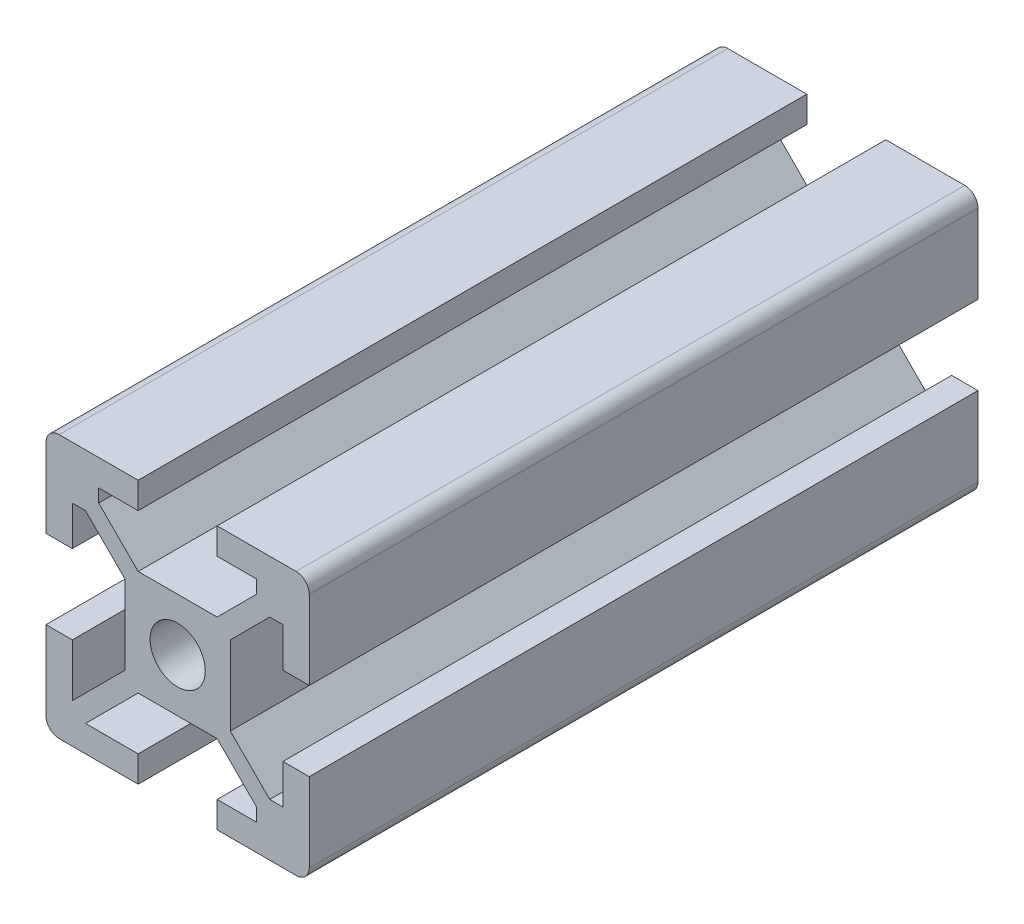
SolidWorks part; units mm, degrees
ref_plane "Front Plane" through (0, 0, 0) normal (0, 0, 1) x (1, 0, 0)
ref_plane "Top Plane" through (0, 0, 0) normal (0, 1, 0) x (1, 0, 0)
ref_plane "Right Plane" through (0, 0, 0) normal (1, 0, 0) x (0, 0, -1)
sketch "Sketch1" plane through (0, 0, 0) normal (0, 0, 1) x (1, 0, 0)
  line L0 (0, 10) -> (0, -10) construction
  line L1 (10, 10) -> (-10, 10)
  line L2 (10, 10) -> (10, -10)
  line L3 (10, -10) -> (-10, -10)
  line L4 (-10, 10) -> (-10, -10)
  line L5 (10, 10) -> (-10, -10) construction
  line L6 (10, -10) -> (-10, 10) construction
  line L7 (-10, 0) -> (10, 0) construction
  line L8 (-4, 3) -> (-8, 7)
  line L9 (6, 6) -> (-6, 6)
  line L10 (6, 6) -> (6, -6)
  line L11 (6, -6) -> (-6, -6)
  line L12 (-6, 6) -> (-6, -6)
  line L13 (6, 6) -> (-6, -6) construction
  line L14 (6, -6) -> (-6, 6) construction
  line L15 (4, 4) -> (-4, 4)
  line L16 (4, 4) -> (4, -4)
  line L17 (4, -4) -> (-4, -4)
  line L18 (-4, 4) -> (-4, -4)
  line L19 (4, 4) -> (-4, -4) construction
  line L20 (4, -4) -> (-4, 4) construction
  line L21 (3, 10) -> (-3, 10)
  line L22 (3, 10) -> (3, -10)
  line L23 (3, -10) -> (-3, -10)
  line L24 (-3, 10) -> (-3, -10)
  line L25 (3, 10) -> (-3, -10) construction
  line L26 (3, -10) -> (-3, 10) construction
  line L27 (10, 3) -> (-10, 3)
  line L28 (10, 3) -> (10, -3)
  line L29 (10, -3) -> (-10, -3)
  line L30 (-10, 3) -> (-10, -3)
  line L31 (10, 3) -> (-10, -3) construction
  line L32 (10, -3) -> (-10, 3) construction
  line L33 (8, 8) -> (-8, 8)
  line L34 (8, 8) -> (8, -8)
  line L35 (8, -8) -> (-8, -8)
  line L36 (-8, 8) -> (-8, -8)
  line L37 (8, 8) -> (-8, -8) construction
  line L38 (8, -8) -> (-8, 8) construction
  line L39 (-3, 4) -> (-7, 8)
  line L40 (3, 4) -> (7, 8)
  line L41 (4, 3) -> (8, 7)
  line L42 (-4, -3) -> (-8, -7)
  line L43 (-3, -4) -> (-7, -8)
  line L44 (3, -4) -> (7, -8)
  line L45 (4, -3) -> (8, -7)
  line L46 (-6, 6) -> (-6, 8)
  line L47 (-6, 6) -> (-8, 6)
  line L48 (-6, -6) -> (-8, -6)
  line L49 (-6, -6) -> (-6, -8)
  line L50 (6, -6) -> (6, -8)
  line L51 (6, -6) -> (8, -6)
  line L52 (6, 6) -> (6, 8)
  line L53 (6, 6) -> (8, 6)
  circle A0 centre (0, 0) radius 2.1
  point P0 (0, 0)
  point P10 (0, 0)
  point P15 (0, 0)
  point P20 (0, 0)
  point P25 (0, 0)
  point P30 (0, 0)
  dimension "D11" = 4.2
  dimension "D1" = 20
  dimension "D2" = 20
  dimension "D3" = 12
  dimension "D4" = 12
  dimension "D5" = 8
  dimension "D6" = 8
  dimension "D7" = 6
  dimension "D8" = 6
  dimension "D9" = 2
  dimension "D10" = 2
extrude "Boss-Extrude1" add sketch "Sketch1" along normal blind 50.8 contours L39 L46 L33 | L47 L46 L39 L33 L36 L8 | L47 L8 L36 | L36 L33 L24 L1 L4 L27 | L12 L47 L8 | L46 L9 L39 | L15 L39 L9 L12 L8 L18 | L27 L24 L15 L18 | L27 L22 L15 L24 | L29 L24 L27 L18 | L29 L22 L27 L24 A0 | L27 L16 L15 L22 | L16 L41 L10 L9 L40 L15 | L9 L52 L40 | L53 L10 L41 | L52 L53 L41 L34 L33 L40 | L52 L40 L33 | L41 L53 L34 | L33 L34 L27 L2 L1 L22 | L29 L16 L27 L22 | L16 L29 L22 L17 | L45 L16 L17 L44 L11 L10 | L10 L51 L45 | L50 L11 L44 | L51 L50 L44 L35 L34 L45 | L44 L50 L35 | L51 L45 L34 | L34 L35 L22 L3 L2 L29 | L22 L29 L24 L17 | L24 L29 L18 L17 | L43 L17 L18 L42 L12 L11 | L11 L49 L43 | L48 L12 L42 | L49 L48 L42 L36 L35 L43 | L36 L29 L4 L3 L24 L35
fillet "Fillet1" radius 1 4 edges at (-10, -10, 25.4) (10, -10, 25.4) (10, 10, 25.4) (-10, 10, 25.4)
